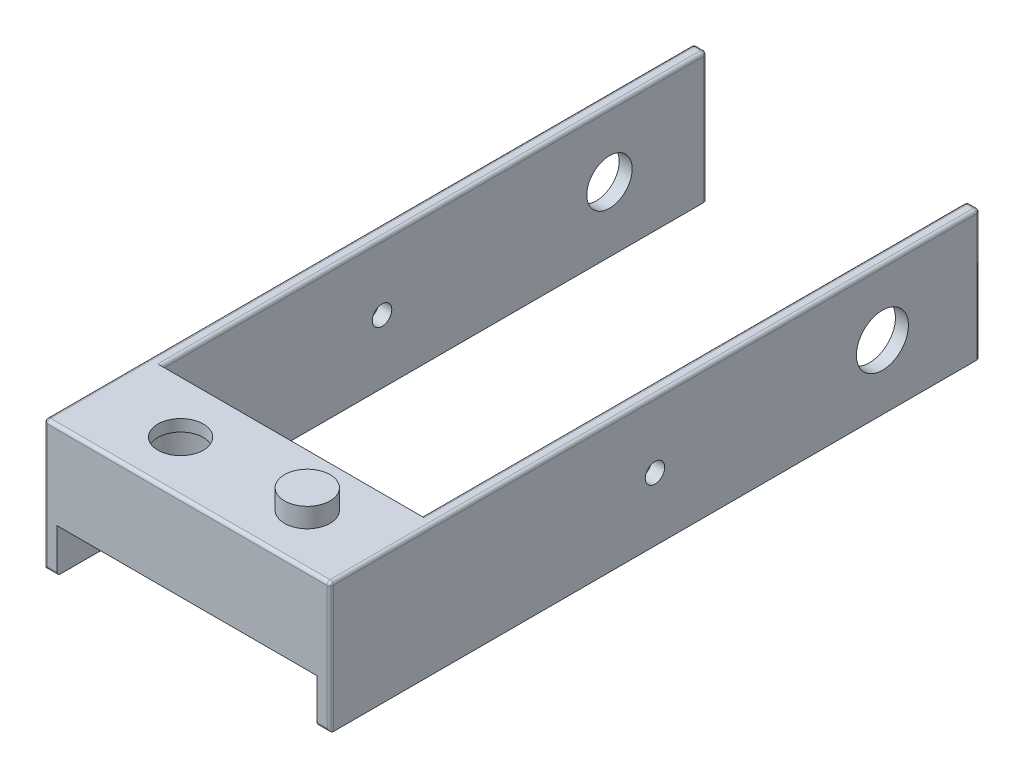
SolidWorks part; units mm, degrees
ref_plane "Front Plane" through (0, 0, 0) normal (0, 0, 1) x (1, 0, 0)
ref_plane "Top Plane" through (0, 0, 0) normal (0, 1, 0) x (1, 0, 0)
ref_plane "Right Plane" through (0, 0, 0) normal (1, 0, 0) x (0, 0, -1)
sketch "Sketch1" plane through (0, 0, 0) normal (0, 1, 0) x (1, 0, 0)
  line L1 (-20, 8) -> (20, 8)
  line L2 (-20, 8) -> (-20, -8)
  line L3 (-20, -8) -> (20, -8)
  line L4 (20, 8) -> (20, -8)
  line L5 (-20, 8) -> (20, -8) construction
  line L6 (-20, -8) -> (20, 8) construction
  point P0 (0, 0)
  dimension "D1" = 16
  dimension "D2" = 40
extrude "Boss-Extrude1" add sketch "Sketch1" along normal blind 13.3
sketch "Sketch2" plane through (0, 0, 0) normal (0, -1, 0) x (1, 0, 0)
  line L0 (-20, -8) -> (-20, 8) construction
  line L1 (-20, 0) -> (-9, 0) construction
  arc A0 (-4.2451, 3.6594) -> (-3.1046, -1.1152) centre (-9, 0) ccw
  arc A2 (-3.1046, -1.1152) -> (-4.2451, 3.6594) centre (-4.1368, 1.1617) ccw
  dimension "D1" = 12
  dimension "D2" = 11
  dimension "D3" = 5
  dimension "D4" = 5
extrude "Cut-Extrude2" cut sketch "Sketch2" against normal blind 11.5
sketch "Sketch3" plane through (0, 0, 0) normal (0, -1, 0) x (-1, 0, 0)
  circle A1 centre (9, 0) radius 3.5
  dimension "D1" = 7
extrude "Cut-Extrude3" cut sketch "Sketch3" against normal blind 24.8
sketch "Sketch4" plane through (0, 0, 0) normal (0, -1, 0) x (-1, 0, 0)
  line L0 (20, 8) -> (20, -8) construction
  line L1 (15, -6) -> (-6, -6)
  line L2 (15, -6) -> (15, 6)
  line L3 (15, 6) -> (-6, 6)
  line L4 (-6, -6) -> (-6, 6)
  line L5 (20, -8) -> (-20, -8) construction
  dimension "D1" = 21
  dimension "D2" = 12
  dimension "D3" = 5
  dimension "D4" = 2
extrude "Cut-Extrude4" cut sketch "Sketch4" against normal blind 4
sketch "Sketch5" plane through (20, 0, 0) normal (1, 0, 0) x (0, 0, -1)
  line L1 (-8, 13.3) -> (92, 13.3)
  line L2 (-8, 13.3) -> (-8, -6.7)
  line L3 (-8, -6.7) -> (92, -6.7)
  line L4 (92, 13.3) -> (92, -6.7)
  dimension "D1" = 100
  dimension "D2" = 20
extrude "Boss-Extrude2" add sketch "Sketch5" along normal blind 2
sketch "Sketch6" plane through (-20, 0, 0) normal (-1, 0, 0) x (0, 0, 1)
  line L0 (8, -6.7) -> (-92, -6.7) construction
  line L1 (8, 13.3) -> (-92, 13.3)
  line L2 (8, 13.3) -> (8, -6.7)
  line L3 (8, -6.7) -> (-92, -6.7)
  line L4 (-92, 13.3) -> (-92, -6.7)
  line L5 (-92, -6.7) -> (-92, 13.3) construction
extrude "Boss-Extrude3" add sketch "Sketch6" along normal blind 2
sketch "Sketch7" plane through (22, 0, 0) normal (1, 0, 0) x (0, 0, -1)
  line L0 (92, -6.7) -> (92, 13.3) construction
  line L1 (92, 3.3) -> (77, 3.2064) construction
  circle A0 centre (77, 3.2064) radius 4
  dimension "D1" = 8
  dimension "D2" = 15
extrude "Cut-Extrude5" cut sketch "Sketch7" against normal up to surface (2 mm away) up to face at (20, 2.2, -30.6667)
sketch "Sketch8" plane through (-20, 0, 0) normal (1, 0, 0) x (0, 0, -1)
  line L0 (-8, 13.3) -> (92, 13.3) construction
  line L1 (92, 13.3) -> (92, -6.7) construction
  circle A0 centre (77, 3.3) radius 3.5
  dimension "D1" = 7
  dimension "D2" = 10
  dimension "D3" = 15
extrude "Cut-Extrude8" cut sketch "Sketch8" against normal up to next
fillet "Fillet1" radius 0.5 4 edges at (20, 13.3, -50) (-20, 13.3, -50) (-22, 13.3, -42) (22, 13.3, -42)
fillet "Fillet2" radius 0.5 19 edges at (-22, 3.05, -92) (-21.8536, 13.1536, -92) (-20, 3.05, -92) (-20.1464, 13.1536, -92) (22, 3.05, -92) (21.8536, 13.1536, -92) (20, 3.05, -92) (20.1464, 13.1536, -92) (-22, 3.05, 8) (-21.8536, 13.1536, 8) (22, 3.05, 8) (21.8536, 13.1536, 8) (-21, 13.3, -92) (21, 13.3, -92) (21, -6.7, -92) (-21, -6.7, -92) (-21, -6.7, 8) (21, -6.7, 8) (0, 13.3, 8)
sketch "Sketch9" plane through (0, 13.3, 0) normal (0, 1, 0) x (1, 0, 0)
  circle A0 centre (10.5, 0) radius 3.5
  circle A1 centre (-9, 0) radius 3.5 construction
  dimension "D1" = 7
  dimension "D2" = 19.5
extrude "Boss-Extrude4" add sketch "Sketch9" along normal blind 3
sketch "Sketch10" plane through (-22, 0, 0) normal (-1, 0, 0) x (0, 0, 1)
  line L0 (-42, 12.8) -> (-42, -6.7) construction
  line L1 (7.5, 12.8) -> (-91.5, 12.8) construction
  line L2 (-91.5, -6.7) -> (7.5, -6.7) construction
  circle A0 centre (-42, 3.05) radius 1.5
extrude "Cut-Extrude9" cut sketch "Sketch10" against normal through all
